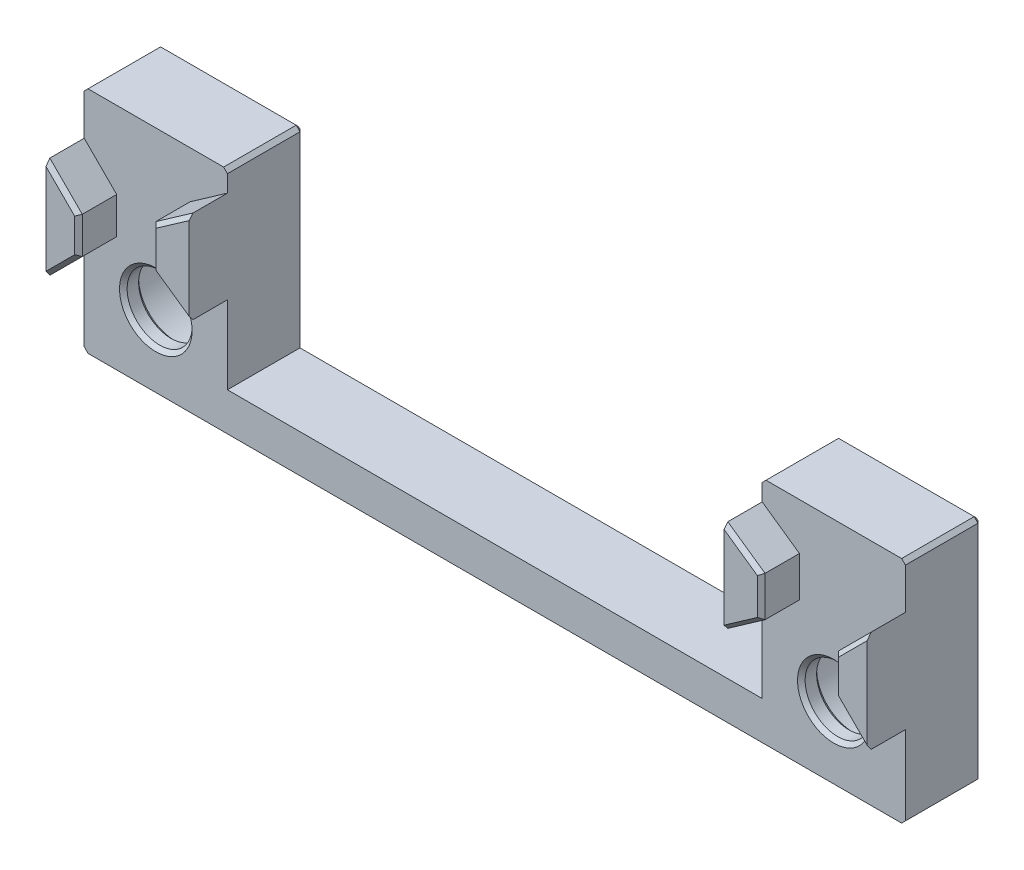
SolidWorks part; units mm, degrees
ref_plane "Front" through (0, 0, 0) normal (0, 0, 1) x (1, 0, 0)
ref_plane "Top" through (0, 0, 0) normal (0, 1, 0) x (1, 0, 0)
ref_plane "Right" through (0, 0, 0) normal (1, 0, 0) x (0, 0, -1)
sketch "Sketch1" plane through (0, 0, 0) normal (0, 0, 1) x (1, 0, 0)
  line L0 (-21.3, -6) -> (21.3, -6)
  line L5 (21.5, -5.8) -> (21.5, 5.8)
  line L6 (21.3, 6) -> (14.2, 6)
  line L7 (14, 5.8) -> (14, -4)
  line L8 (14, -4) -> (-14, -4)
  line L9 (-14, -4) -> (-14, 5.8)
  line L10 (-14.2, 6) -> (-21.3, 6)
  line L11 (-21.5, 5.8) -> (-21.5, -5.8)
  line L12 (21.5, 5.8) -> (21.5, -5.8) construction
  line L13 (21.3, 6) -> (14, 6) construction
  line L14 (21.3, -6) -> (-21.3, -6) construction
  line L15 (21.5, 5.8) -> (21.3, 6)
  line L16 (-14, 6) -> (-21.3, 6) construction
  line L17 (-21.5, 5.8) -> (-21.5, -5.8) construction
  line L18 (14.2, 6) -> (14, 5.8)
  line L19 (21.3, -6) -> (21.5, -5.8)
  line L20 (-21.5, -5.8) -> (-21.3, -6)
  line L21 (-21.3, 6) -> (-21.5, 5.8)
  line L22 (-14, 5.8) -> (-14.2, 6)
  point P0 (-21.5, -6)
  point P1 (21.5, -6)
  point P2 (21.5, 6)
  point P4 (14, 6)
  point P6 (-21.5, 6)
  point P13 (-14, 6)
  dimension "D1" = 45
  dimension "D3" = 45
  dimension "D6" = 0.2
  dimension "D5" = 45
  dimension "D7" = 45
  dimension "D12" = 0.2
  dimension "D8" = 45
  dimension "D11" = 0.2
  dimension "D9" = 0.2
  dimension "D10" = 45
  dimension "D2" = 0.2
  dimension "D4" = 0.2
extrude "Boss-Extrude1" add sketch "Sketch1" against normal blind 4
sketch "Sketch3" plane through (0, 0, 0) normal (0, 0, 1) x (1, 0, 0)
  line L1 (13.75, -0.0929) -> (15.95, 1.4475) construction
  line L7 (15.95, 1.4475) -> (15.95, 3.5525) construction
  line L8 (15.95, 3.5525) -> (13.75, 5.0929) construction
  line L9 (13.75, 5.0929) -> (11.55, 3.5525) construction
  line L10 (11.55, 3.5525) -> (11.55, 1.4475) construction
  line L11 (11.55, 1.4475) -> (13.75, -0.0929) construction
  line L12 (16.1, 1.3694) -> (16.1, 3.6306)
  line L13 (16.1, 3.6306) -> (13.75, 5.276)
  line L14 (13.75, 5.276) -> (11.4, 3.6306)
  line L16 (11.4, 3.6306) -> (11.4, 1.3694)
  line L30 (11.4, 1.3694) -> (13.75, -0.276)
  line L32 (13.75, -0.276) -> (16.1, 1.3694)
  line L36 (16.1, 1.3694) -> (16.1, 3.6306) construction
  line L46 (16.1, 3.6306) -> (13.75, 5.276) construction
  line L47 (13.75, 5.276) -> (11.4, 3.6306) construction
  line L48 (11.4, 3.6306) -> (11.4, 1.3694) construction
  line L49 (11.4, 1.3694) -> (13.75, -0.276) construction
  line L50 (13.75, -0.276) -> (16.1, 1.3694) construction
  line L51 (14, 4.9179) -> (14, 0.0821)
  line L52 (14, 0.0821) -> (15.95, 1.4475)
  line L53 (15.95, 1.4475) -> (15.95, 3.5525)
  line L54 (15.95, 3.5525) -> (14, 4.9179)
  line L55 (14, 6) -> (14, 5.101) construction
  dimension "D1" = 0
  dimension "D2" = 0.15
extrude "Slot Aligner" add sketch "Sketch3" along normal blind 2
mirror "Mirror3" about plane through (0, 0, 0) normal (1, 0, 0) of "Slot Aligner"
sketch "Sketch4" plane through (0, 0, 0) normal (0, 0, -1) x (-1, 0, 0)
  line L8 (-19.8, 1.9586) -> (-21.4, 3.5586)
  line L10 (-21.4, -1.5586) -> (-19.8, 0.0414)
  line L11 (-19.8, 0.0414) -> (-19.8, 1.9586)
  line L21 (-21.5, -1.8) -> (-19.7, 0)
  line L25 (-19.7, 0) -> (-19.7, 2)
  line L26 (-19.7, 2) -> (-21.5, 3.8)
  line L27 (-21.5, 3.8) -> (-21.5, -1.8)
  line L28 (-21.5, -1.8) -> (-19.7, 0) construction
  line L29 (-19.7, 0) -> (-19.7, 2) construction
  line L30 (-19.7, 2) -> (-21.5, 3.8) construction
  line L31 (-21.5, 3.8) -> (-21.5, -1.8) construction
  line L32 (-21.4, 3.5586) -> (-21.5, 3.6586)
  line L33 (-21.5, 3.6586) -> (-21.5, -1.6586)
  line L34 (-21.5, -1.6586) -> (-21.4, -1.5586)
  line L36 (-21.4, 3.5586) -> (-21.4, -1.5586) construction
  dimension "D1" = 0
  dimension "D2" = 0.1
extrude "Aligner" add sketch "Sketch4" against normal blind 2
mirror "Aligners" about plane through (0, 0, 0) normal (1, 0, 0) of "Aligner"
chamfer "Deburs" distance 0.2 angle 45 26 edges at (14, 0.9, -4) (14.1, 5.9, -4) (17.75, 6, -4) (21.4, 5.9, -4) (21.5, 0, -4) (21.4, -5.9, -4) (0, -6, -4) (-21.4, -5.9, -4) (-21.5, 0, -4) (-21.4, 5.9, -4) (-17.75, 6, -4) (-14.1, 5.9, -4) (-14, 0.9, -4) (0, -4, -4) (20.65, -0.8086, 2) (20.65, 2.8086, 2) (19.8, 1, 2) (14.975, 4.2352, 2) (15.95, 2.5, 2) (14.975, 0.7648, 2) (-14.975, 4.2352, 2) (-15.95, 2.5, 2) (-14.975, 0.7648, 2) (-20.65, 2.8086, 2) (-20.65, -0.8086, 2) (-19.8, 1, 2)
sketch "Sketch5" plane through (0, 0, -4) normal (0, 0, -1) x (-1, 0, 0)
  point P0 (-17.75, -2.25)
  point P1 (17.75, -2.25)
hole_wizard "CBORE for M3 SHCS1" positions "Sketch5" profile "Sketch6" counterbore size "M3" standard "ANSI Metric" end condition through all
sketch "Sketch6" plane through (17.75, -2.25, -4) normal (1, 0, 0) x (0, 1, 0)
  line L0 (0, 0) -> (0, 6)
  line L1 (0, 6) -> (1.7, 6)
  line L3 (1.7, 6) -> (1.7, 3)
  line L4 (1.7, 3) -> (3.25, 3)
  line L5 (3.25, 3) -> (3.25, 0)
  line L7 (3.25, 0) -> (0, 0)
  line L11 (0, -6.35) -> (0, 107.95) construction
  dimension "Thru Hole Dia." = 3.4
  dimension "Thru Hole Depth" = 6
  dimension "C'Bore Dia." = 6.5
  dimension "C'Bore Depth" = 3
chamfer "Chamfer1" distance 0.2 angle 45 6 edges at (-19.45, -2.25, 0) (-19.45, -2.25, -1) (16.05, -2.25, 0) (16.05, -2.25, -1) (14.5, -2.25, -4) (-21, -2.25, -4)
